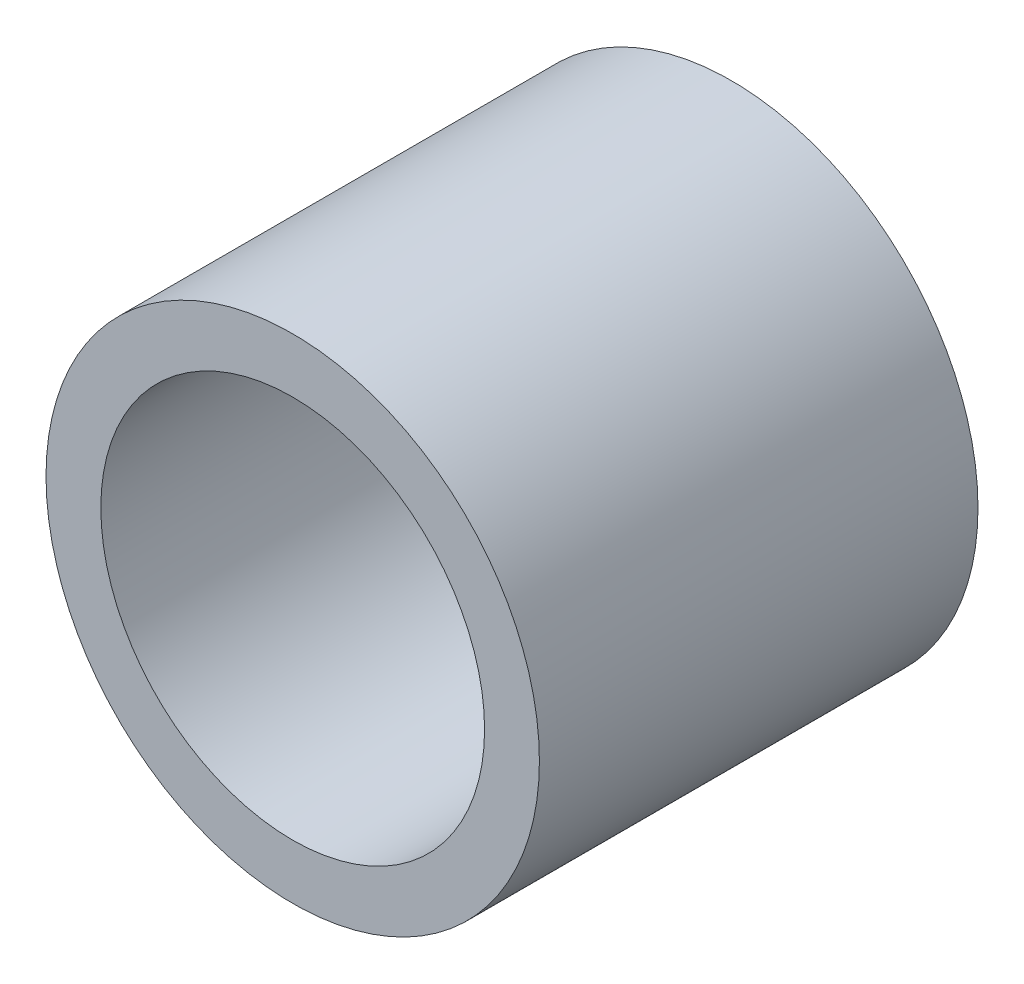
SolidWorks part; units mm, degrees
ref_plane "Front Plane" through (0, 0, 0) normal (0, 0, 1) x (1, 0, 0)
ref_plane "Top Plane" through (0, 0, 0) normal (0, 1, 0) x (1, 0, 0)
ref_plane "Right Plane" through (0, 0, 0) normal (1, 0, 0) x (0, 0, -1)
sketch "Sketch1" plane through (0, 0, 0) normal (0, 0, 1) x (1, 0, 0)
  circle A0 centre (0, 0) radius 22.225
  circle A1 centre (0, 0) radius 28.575
  dimension "D1" = 44.45
  dimension "D2" = 57.15
extrude "Boss-Extrude1" add sketch "Sketch1" along normal blind 50.8
